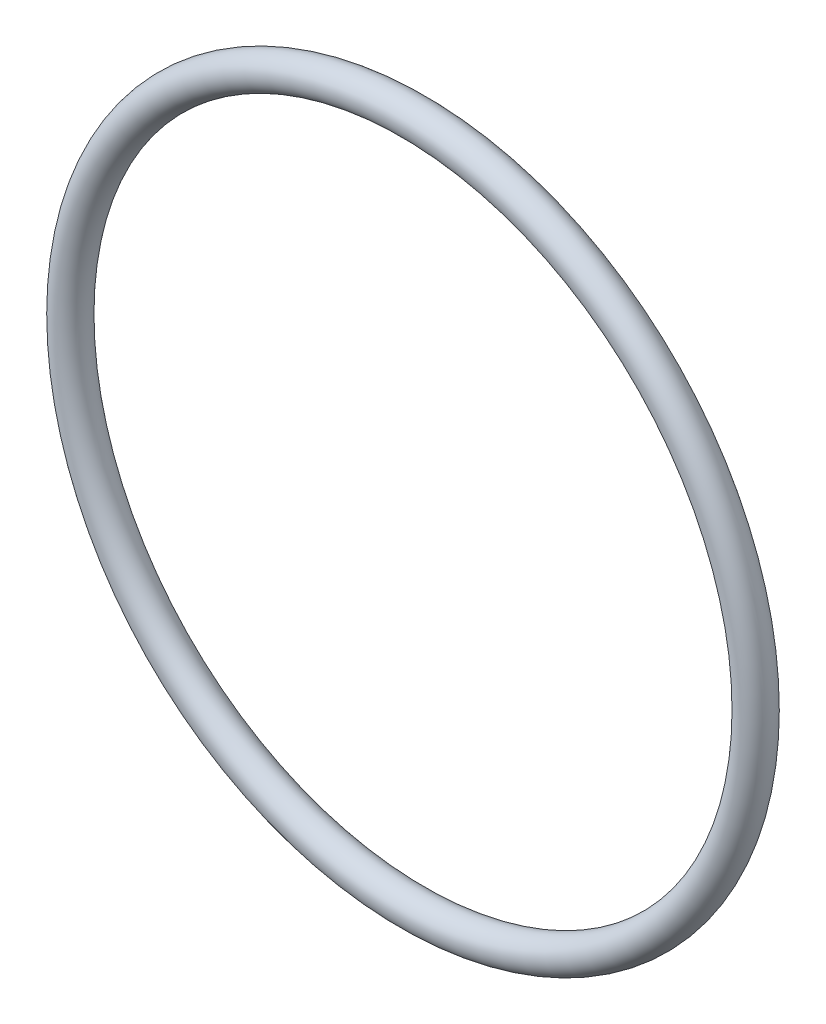
SolidWorks part; units mm, degrees
ref_plane "Front" through (0, 0, 0) normal (0, 0, 1) x (1, 0, 0)
ref_plane "Top" through (0, 0, 0) normal (0, 1, 0) x (1, 0, 0)
ref_plane "Right" through (0, 0, 0) normal (1, 0, 0) x (0, 0, -1)
sketch "Sketch1" plane through (0, 0, 0) normal (1, 0, 0) x (0, -1, 0)
  line L0 (0, -0.889) -> (0, 0.889) construction
  line L2 (-20.1308, 0) -> (20.1308, 0) construction
  line L3 (-17.3228, 0) -> (17.3228, 0) construction
  circle A0 centre (18.2118, 0) radius 0.889
  point P9 (17.3228, 0)
  point P10 (19.1008, 0)
  point P13 (18.2118, 0.889)
  point P14 (18.2118, -0.889)
  dimension "Width" = 1.778
  dimension "ID" = 34.6456
revolve "Revolve1" add sketch "Sketch1" angle 360 about L0
